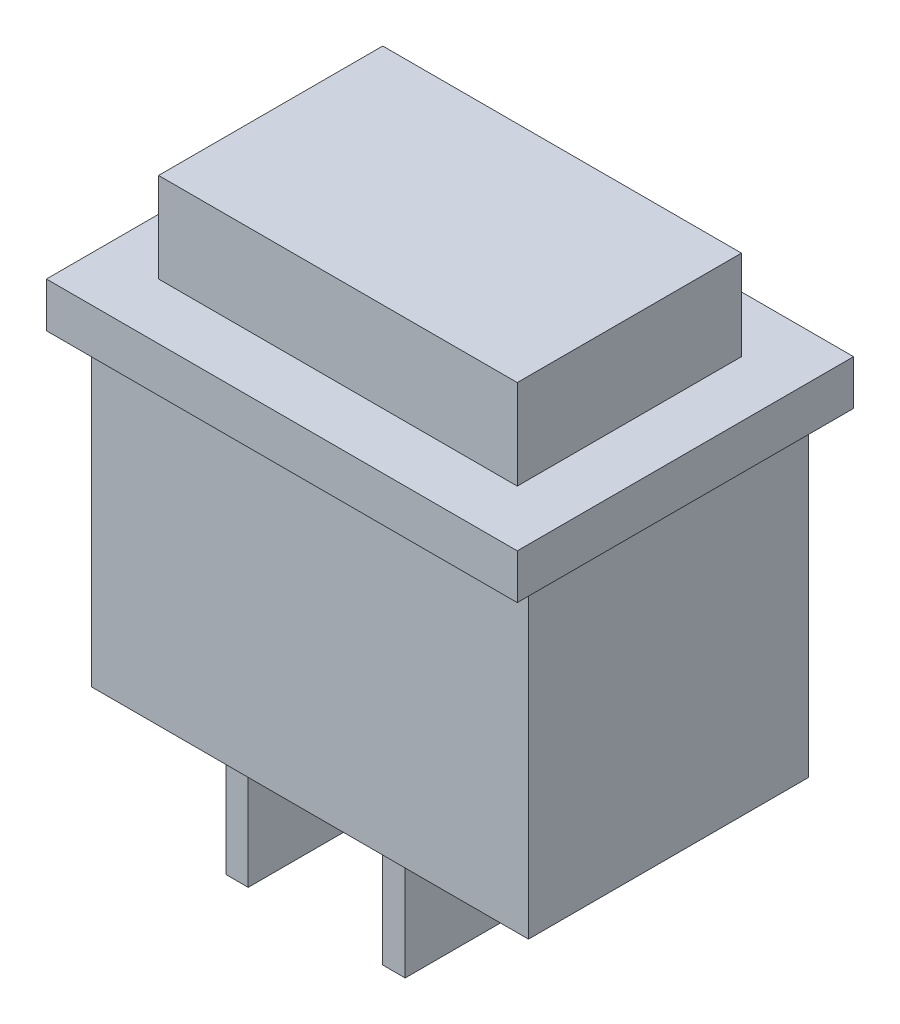
SolidWorks part; units mm, degrees
ref_plane "Front" through (0, 0, 0) normal (0, 0, 1) x (1, 0, 0)
ref_plane "Top" through (0, 0, 0) normal (0, 1, 0) x (1, 0, 0)
ref_plane "Right" through (0, 0, 0) normal (1, 0, 0) x (0, 0, -1)
sketch "Эскиз1" plane through (0, 0, 0) normal (0, 1, 0) x (1, 0, 0)
  line L1 (-10.5, 7.5) -> (10.5, 7.5)
  line L2 (-10.5, 7.5) -> (-10.5, -7.5)
  line L3 (-10.5, -7.5) -> (10.5, -7.5)
  line L4 (10.5, 7.5) -> (10.5, -7.5)
  line L5 (-10.5, 7.5) -> (10.5, -7.5) construction
  line L6 (-10.5, -7.5) -> (10.5, 7.5) construction
  point P0 (0, 0)
  dimension "D1" = 21
  dimension "D2" = 15
extrude "Бобышка-Вытянуть1" add sketch "Эскиз1" along normal blind 2
sketch "Эскиз2" plane through (0, 2, 0) normal (0, 1, 0) x (1, 0, 0)
  line L1 (-8, 5) -> (8, 5)
  line L2 (-8, 5) -> (-8, -5)
  line L3 (-8, -5) -> (8, -5)
  line L4 (8, 5) -> (8, -5)
  line L5 (-8, 5) -> (8, -5) construction
  line L6 (-8, -5) -> (8, 5) construction
  point P0 (0, 0)
  dimension "D1" = 10
  dimension "D2" = 16
extrude "Бобышка-Вытянуть2" add sketch "Эскиз2" along normal blind 4
sketch "Эскиз3" plane through (0, 0, 0) normal (0, -1, 0) x (1, 0, 0)
  line L1 (-9.75, 6.25) -> (9.75, 6.25)
  line L2 (-9.75, 6.25) -> (-9.75, -6.25)
  line L3 (-9.75, -6.25) -> (9.75, -6.25)
  line L4 (9.75, 6.25) -> (9.75, -6.25)
  line L5 (-9.75, 6.25) -> (9.75, -6.25) construction
  line L6 (-9.75, -6.25) -> (9.75, 6.25) construction
  point P0 (0, 0)
  dimension "D1" = 12.5
  dimension "D2" = 19.5
extrude "Бобышка-Вытянуть3" add sketch "Эскиз3" along normal blind 14
sketch "Эскиз4" plane through (0, -14, 0) normal (0, -1, 0) x (1, 0, 0)
  line L0 (-9.75, 0) -> (9.75, 0) construction
  line L1 (-9.75, 6.25) -> (-9.75, -6.25) construction
  line L2 (9.75, -6.25) -> (9.75, 6.25) construction
  line L4 (-7.5, -2.5) -> (-6.5, -2.5)
  line L5 (-7.5, -2.5) -> (-7.5, 2.5)
  line L6 (-7.5, 2.5) -> (-6.5, 2.5)
  line L7 (-6.5, -2.5) -> (-6.5, 2.5)
  line L8 (-7.5, -2.5) -> (-6.5, 2.5) construction
  line L9 (-7.5, 2.5) -> (-6.5, -2.5) construction
  line L10 (-0.5, -2.5) -> (0.5, -2.5)
  line L11 (-0.5, -2.5) -> (-0.5, 2.5)
  line L12 (-0.5, 2.5) -> (0.5, 2.5)
  line L13 (0.5, -2.5) -> (0.5, 2.5)
  line L14 (-0.5, -2.5) -> (0.5, 2.5) construction
  line L15 (-0.5, 2.5) -> (0.5, -2.5) construction
  point P6 (-7, 0)
  point P11 (0, 0)
  dimension "D1" = 1
  dimension "D2" = 5
  dimension "D4" = 6
extrude "Бобышка-Вытянуть4" add sketch "Эскиз4" along normal blind 8
